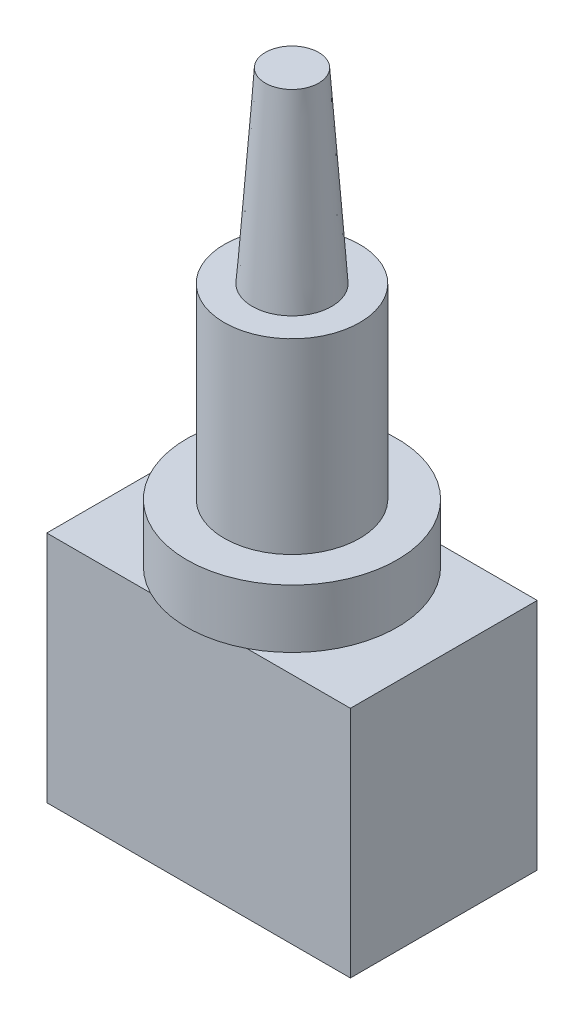
SolidWorks part; units mm, degrees
ref_plane "Plan de face" through (0, 0, 0) normal (0, 0, 1) x (1, 0, 0)
ref_plane "Plan de dessus" through (0, 0, 0) normal (0, 1, 0) x (1, 0, 0)
ref_plane "Plan de droite" through (0, 0, 0) normal (1, 0, 0) x (0, 0, -1)
sketch "Esquisse1" plane through (0, 0, 0) normal (0, 1, 0) x (1, 0, 0)
  line L1 (-6.5, 4) -> (6.5, 4)
  line L2 (-6.5, 4) -> (-6.5, -4)
  line L3 (-6.5, -4) -> (6.5, -4)
  line L4 (6.5, 4) -> (6.5, -4)
  line L5 (-6.5, 4) -> (6.5, -4) construction
  line L6 (-6.5, -4) -> (6.5, 4) construction
  point P0 (0, 0)
  dimension "D1" = 13
  dimension "D2" = 8
extrude "Boss.-Extru.1" add sketch "Esquisse1" along normal blind 10
sketch "Esquisse2" plane through (0, 10, 0) normal (0, 1, 0) x (1, 0, 0)
  circle A0 centre (0, 0) radius 4.5
  dimension "D1" = 9
extrude "Boss.-Extru.2" add sketch "Esquisse2" along normal blind 2.5
sketch "Esquisse3" plane through (0, 12.5, 0) normal (0, 1, 0) x (1, 0, 0)
  circle A0 centre (0, 0) radius 2.9
  dimension "D1" = 5.8
extrude "Boss.-Extru.3" add sketch "Esquisse3" along normal blind 8
sketch "Esquisse4" plane through (0, 20.5, 0) normal (0, 1, 0) x (1, 0, 0)
  circle A0 centre (0, 0) radius 1.7
  dimension "D1" = 3.4
extrude "Boss.-Extru.4" add sketch "Esquisse4" along normal blind 8 draft 4
